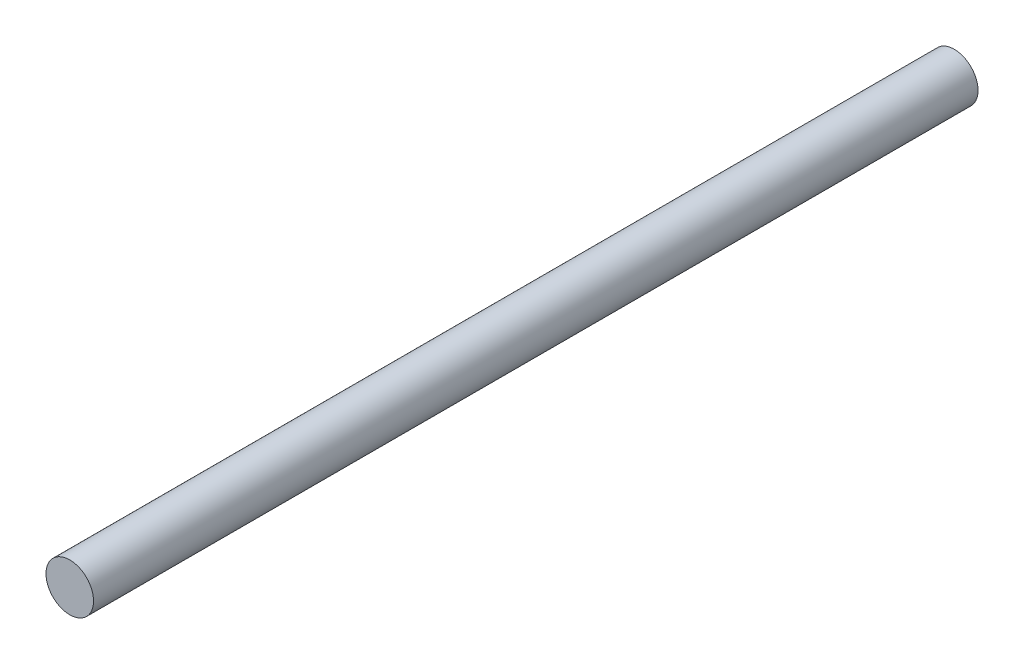
SolidWorks part; units mm, degrees
ref_plane "Front Plane" through (0, 0, 0) normal (0, 0, 1) x (1, 0, 0)
ref_plane "Top Plane" through (0, 0, 0) normal (0, 1, 0) x (1, 0, 0)
ref_plane "Right Plane" through (0, 0, 0) normal (1, 0, 0) x (0, 0, -1)
sketch "Sketch1" plane through (0, 0, 0) normal (0, 0, 1) x (1, 0, 0)
  circle A0 centre (0, 0) radius 2.5
  dimension "D1" = 5
extrude "Boss-Extrude1" add sketch "Sketch1" along normal blind 93
